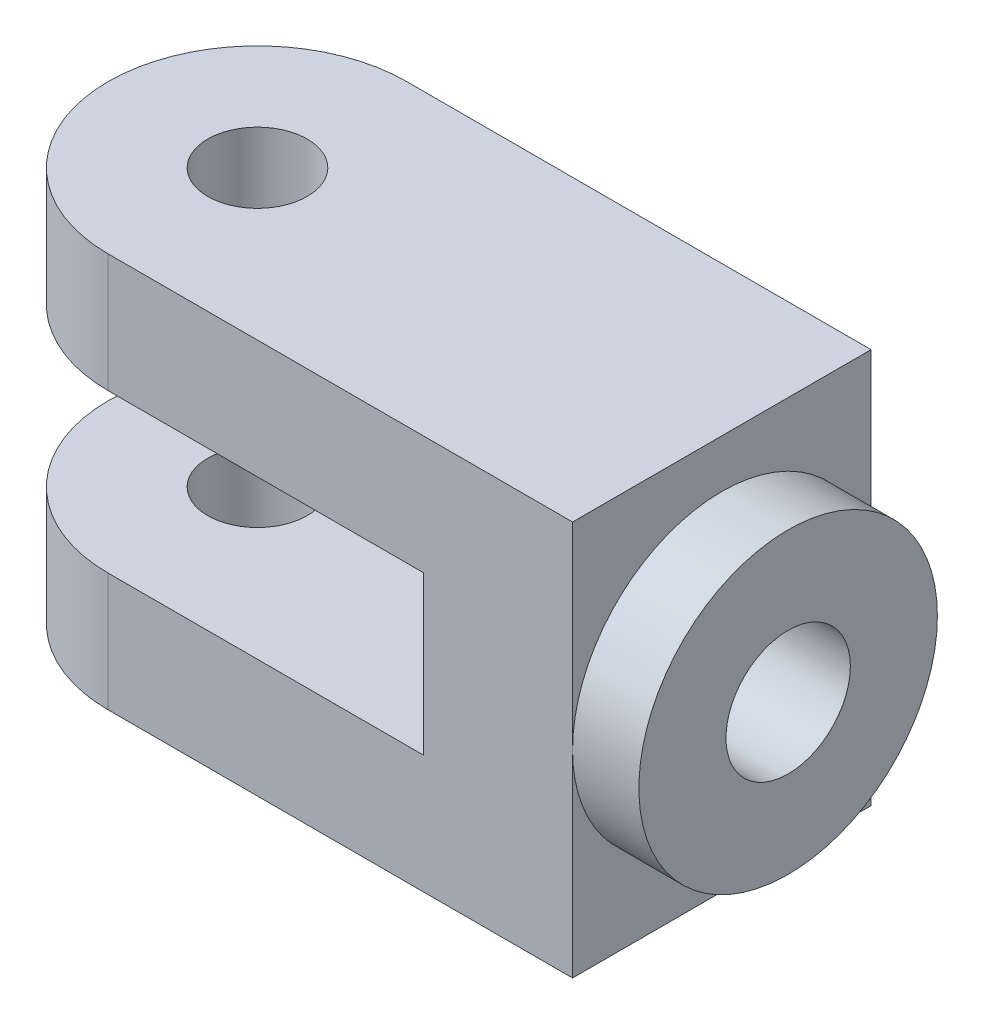
SolidWorks part; units mm, degrees
ref_plane "Front Plane" through (0, 0, 0) normal (0, 0, 1) x (1, 0, 0)
ref_plane "Top Plane" through (0, 0, 0) normal (0, 1, 0) x (1, 0, 0)
ref_plane "Right Plane" through (0, 0, 0) normal (1, 0, 0) x (0, 0, -1)
sketch "Sketch1" plane through (0, 0, 0) normal (0, 1, 0) x (1, 0, 0)
  line L0 (0, 0) -> (0, 100141.5358) construction
  line L1 (0, 0) -> (100141.5358, 0) construction
  line L2 (0, -36) -> (0, 36)
  line L3 (0, 36) -> (-112, 36)
  line L4 (-112, -36) -> (0, -36)
  arc A0 (-112, 36) -> (-112, -36) centre (-112, 0) ccw
  circle A1 centre (-112, 0) radius 12
  point P8 (0, 0)
  dimension "D3" = 24
  dimension "D1" = 72
  dimension "D2" = 112
extrude "Boss-Extrude1" add sketch "Sketch1" along normal mid plane 95.25
sketch "Sketch2" plane through (0, 0, 0) normal (1, 0, 0) x (0, 0, -1)
  line L0 (36, 47.625) -> (36, -47.625) construction
  line L1 (36, 19.05) -> (-36, 19.05)
  line L2 (36, 19.05) -> (36, -19.05)
  line L3 (36, -19.05) -> (-36, -19.05)
  line L4 (-36, 19.05) -> (-36, -19.05)
  line L5 (-36, 47.625) -> (-36, -47.625) construction
  point P6 (36, 0)
  dimension "D1" = 38.1
extrude "Cut-Extrude1" cut sketch "Sketch2" against normal through all from offset 36 offset against normal yes
sketch "Sketch3" plane through (0, 0, 0) normal (1, 0, 0) x (0, 0, -1)
  circle A0 centre (0, 0) radius 36
  dimension "D1" = 72
extrude "Boss-Extrude2" add sketch "Sketch3" along normal blind 16
sketch "Sketch4" plane through (16, 0, 0) normal (1, 0, 0) x (0, 0, -1)
  circle A0 centre (0, 0) radius 15
  dimension "D1" = 30
extrude "Cut-Extrude2" cut sketch "Sketch4" against normal through all
